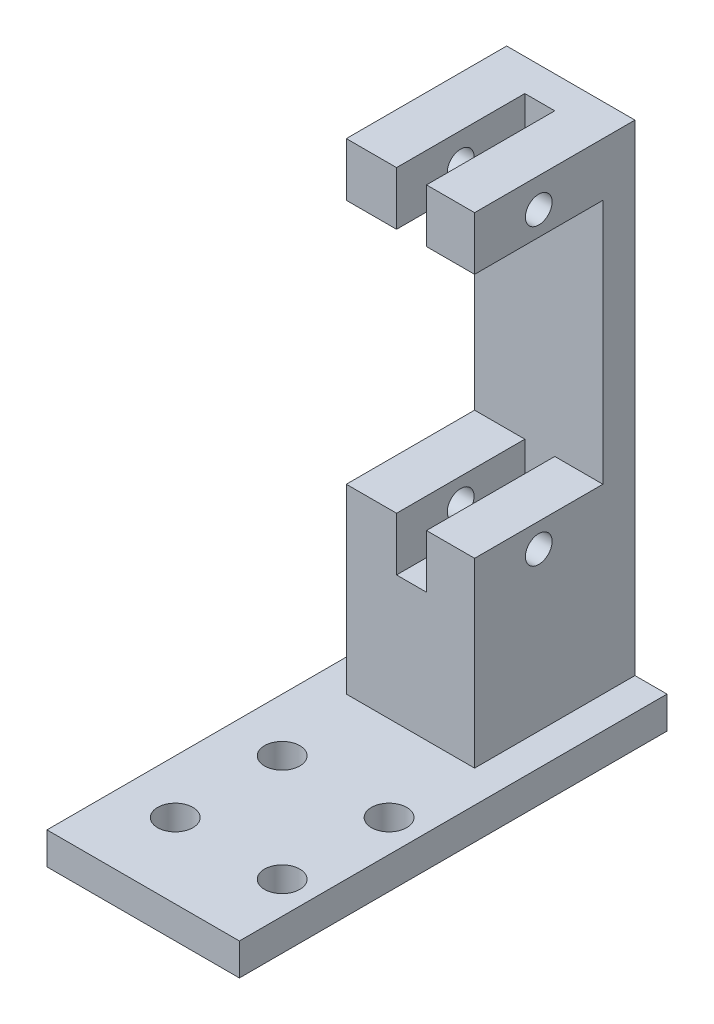
SolidWorks part; units mm, degrees
ref_plane "前视基准面" through (0, 0, 0) normal (0, 0, 1) x (1, 0, 0)
ref_plane "上视基准面" through (0, 0, 0) normal (0, 1, 0) x (1, 0, 0)
ref_plane "右视基准面" through (0, 0, 0) normal (1, 0, 0) x (0, 0, -1)
sketch "草图1" plane through (0, 0, 0) normal (0, 0, 1) x (1, 0, 0)
  line L1 (-6, 20) -> (6, 20)
  line L2 (-6, 20) -> (-6, -20)
  line L3 (-6, -20) -> (6, -20)
  line L4 (6, 20) -> (6, -20)
  line L5 (-6, 20) -> (6, -20) construction
  line L6 (-6, -20) -> (6, 20) construction
  point P0 (0, 0)
  dimension "D1" = 40
  dimension "D2" = 12
extrude "凸台-拉伸1" add sketch "草图1" along normal blind 3 contours L2 L1 L4 L3
sketch "草图2" plane through (0, 0, 3) normal (0, 0, 1) x (1, 0, 0)
  line L0 (6, 20) -> (6, -20) construction
  line L1 (1.5, 20) -> (6, 20)
  line L2 (1.5, 20) -> (1.5, 15)
  line L3 (1.5, 15) -> (6, 15)
  line L4 (6, 20) -> (6, 15)
  line L5 (1.5, 20) -> (6, 15) construction
  line L6 (1.5, 15) -> (6, 20) construction
  line L7 (-6, 20) -> (6, 20) construction
  line L9 (-6, 20) -> (-1.3, 20)
  line L10 (-6, 20) -> (-6, 15)
  line L11 (-6, 15) -> (-1.3, 15)
  line L12 (-1.3, 20) -> (-1.3, 15)
  line L15 (-6, -8) -> (-1.3, -8)
  line L16 (-1.3, -13) -> (-1.3, -8)
  line L17 (6, -8) -> (6, -20)
  line L20 (6, -8) -> (1.5, -8)
  line L21 (1.5, -13) -> (1.5, -8)
  line L26 (-6, -20) -> (6, -20)
  line L28 (-1.3, -13) -> (1.5, -13)
  line L30 (-6, -8) -> (-6, -20)
  point P0 (3.75, 17.5)
  point P13 (-1.3, 17.5)
  point P25 (3.75, -8)
  point P28 (-3.65, -8)
  dimension "D1" = 4.5
  dimension "D2" = 5
  dimension "D3" = 2.8
  dimension "D4" = 5
  dimension "D5" = 12
  dimension "D6" = 5
  dimension "D7" = 4.5
  dimension "D9" = 23
extrude "凸台-拉伸2" add sketch "草图2" along normal blind 12
sketch "草图3" plane through (6, 0, 0) normal (1, 0, 0) x (0, 0, -1)
  line L0 (-3, 15) -> (-3, -8) construction
  line L1 (-15, 20) -> (0, 20) construction
  line L5 (-15, -8) -> (-3, -8) construction
  circle A0 centre (-9, 17.25) radius 1.25
  circle A1 centre (-9, -10.25) radius 1.25
  dimension "D1" = 2.5
  dimension "D4" = 2.5
  dimension "D2" = 6
  dimension "D3" = 2.75
  dimension "D5" = 6
  dimension "D6" = 2.25
extrude "切除-拉伸1" cut sketch "草图3" against normal blind 12
sketch "草图4" plane through (0, -20, 0) normal (0, -1, 0) x (1, 0, 0)
  line L1 (-6, 15) -> (6, 15)
  line L2 (-6, 15) -> (-6, 0)
  line L3 (-6, 0) -> (6, 0)
  line L4 (6, 15) -> (6, 0)
extrude "凸台-拉伸3" add sketch "草图4" along normal blind 8
sketch "草图5" plane through (0, 0, 15) normal (0, 0, 1) x (1, 0, 0)
  line L0 (-6, -8) -> (-6, -28) construction
  line L1 (-6, -25) -> (6, -25)
  line L2 (-6, -25) -> (-6, -28)
  line L3 (-6, -28) -> (6, -28)
  line L4 (6, -25) -> (6, -28)
  dimension "D1" = 3
extrude "凸台-拉伸4" add sketch "草图5" along normal blind 25
sketch "草图6" plane through (6, 0, 0) normal (1, 0, 0) x (0, 0, -1)
  line L1 (-40, -25) -> (0, -25)
  line L2 (-40, -25) -> (-40, -28)
  line L3 (-40, -28) -> (0, -28)
  line L4 (0, -25) -> (0, -28)
extrude "凸台-拉伸5" add sketch "草图6" along normal blind 3
sketch "草图7" plane through (0, -25, 0) normal (0, 1, 0) x (1, 0, 0)
  line L1 (9, 0) -> (9, -40) construction
  line L3 (6, -15) -> (1.5, -15) construction
  circle A0 centre (6, -23) radius 1.65
  circle A1 centre (6, -33) radius 1.65
  circle A2 centre (-4, -23) radius 1.65
  circle A3 centre (-4, -33) radius 1.65
  dimension "D1" = 3.3
  dimension "D2" = 3.3
  dimension "D5" = 3.3
  dimension "D6" = 3.3
  dimension "D3" = 10
  dimension "D4" = 3
  dimension "D7" = 10
  dimension "D8" = 8
extrude "切除-拉伸2" cut sketch "草图7" against normal blind 3
sketch "草图8" plane through (-6, 0, 0) normal (-1, 0, 0) x (0, 0, 1)
  line L1 (40, -25) -> (0, -25)
  line L2 (40, -25) -> (40, -28)
  line L3 (40, -28) -> (0, -28)
  line L4 (0, -25) -> (0, -28)
extrude "凸台-拉伸6" add sketch "草图8" along normal blind 3
